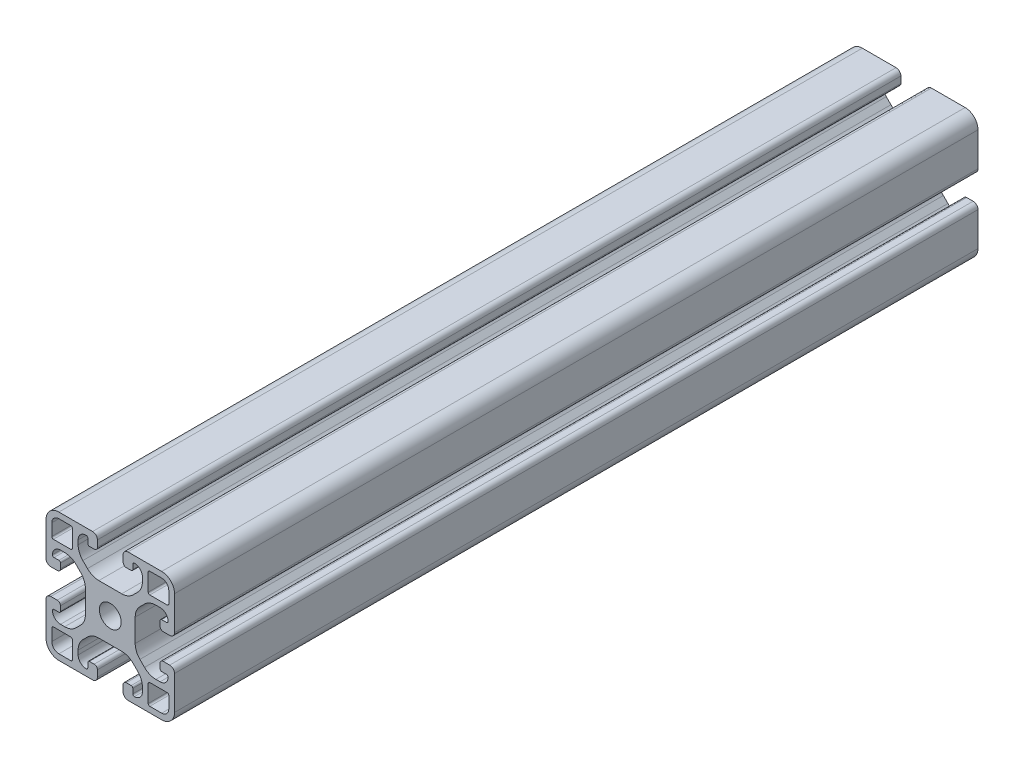
SolidWorks part; units mm, degrees
ref_plane "Front Plane" through (0, 0, 0) normal (0, 0, 1) x (1, 0, 0)
ref_plane "Top Plane" through (0, 0, 0) normal (0, 1, 0) x (1, 0, 0)
ref_plane "Right Plane" through (0, 0, 0) normal (1, 0, 0) x (0, 0, -1)
sketch "Sketch1" plane through (0, 0, 0) normal (0, 0, 1) x (1, 0, 0)
  line L0 (1.8, 4) -> (1.8, 7.7)
  line L1 (2.3, 8.2) -> (7.7, 8.2)
  line L2 (8.2, 7.7) -> (8.2, 2.3)
  line L3 (7.7, 1.8) -> (4, 1.8)
  line L4 (4, 38.2) -> (7.7, 38.2)
  line L5 (8.2, 37.7) -> (8.2, 32.3)
  line L6 (7.7, 31.8) -> (2.3, 31.8)
  line L7 (1.8, 32.3) -> (1.8, 36)
  line L8 (31.8, 32.3) -> (31.8, 37.7)
  line L9 (32.3, 38.2) -> (36, 38.2)
  line L10 (38.2, 36) -> (38.2, 32.3)
  line L11 (37.7, 31.8) -> (32.3, 31.8)
  line L12 (32.3, 8.2) -> (37.7, 8.2)
  line L13 (38.2, 7.7) -> (38.2, 4)
  line L14 (36, 1.8) -> (32.3, 1.8)
  line L15 (31.8, 2.3) -> (31.8, 7.7)
  line L16 (0, 36) -> (0, 25.5)
  line L17 (1.5, 24) -> (3.5, 24)
  line L18 (4.5, 25) -> (4.5, 26.5)
  line L19 (4, 27) -> (2.5, 27)
  line L20 (4.5, 30) -> (5.8076, 30)
  line L21 (9.3431, 28.5355) -> (10.7855, 27.0931)
  line L22 (12.25, 23.5576) -> (12.25, 16.4424)
  line L23 (10.7855, 12.9069) -> (9.3431, 11.4645)
  line L24 (5.8076, 10) -> (4.5, 10)
  line L25 (2.5, 13) -> (4, 13)
  line L26 (4.5, 13.5) -> (4.5, 15)
  line L27 (3.5, 16) -> (1.5, 16)
  line L28 (0, 14.5) -> (0, 4)
  line L29 (4, 0) -> (14.5, 0)
  line L30 (16, 1.5) -> (16, 3.5)
  line L31 (15, 4.5) -> (13.5, 4.5)
  line L32 (13, 4) -> (13, 2.5)
  line L33 (10, 4.5) -> (10, 5.8076)
  line L34 (11.4645, 9.3431) -> (12.9069, 10.7855)
  line L35 (16.4424, 12.25) -> (23.5576, 12.25)
  line L36 (27.0931, 10.7855) -> (28.5355, 9.3431)
  line L37 (30, 5.8076) -> (30, 4.5)
  line L38 (27, 2.5) -> (27, 4)
  line L39 (26.5, 4.5) -> (25, 4.5)
  line L40 (24, 3.5) -> (24, 1.5)
  line L41 (25.5, 0) -> (36, 0)
  line L42 (40, 4) -> (40, 14.5)
  line L43 (38.5, 16) -> (36.5, 16)
  line L44 (35.5, 15) -> (35.5, 13.5)
  line L45 (36, 13) -> (37.5, 13)
  line L46 (35.5, 10) -> (34.1924, 10)
  line L47 (30.6569, 11.4645) -> (29.2145, 12.9069)
  line L48 (27.75, 16.4424) -> (27.75, 23.5576)
  line L49 (29.2145, 27.0931) -> (30.6569, 28.5355)
  line L50 (34.1924, 30) -> (35.5, 30)
  line L51 (37.5, 27) -> (36, 27)
  line L52 (35.5, 26.5) -> (35.5, 25)
  line L53 (36.5, 24) -> (38.5, 24)
  line L54 (40, 25.5) -> (40, 36)
  line L55 (36, 40) -> (25.5, 40)
  line L56 (24, 38.5) -> (24, 36.5)
  line L57 (25, 35.5) -> (26.5, 35.5)
  line L58 (27, 36) -> (27, 37.5)
  line L59 (30, 35.5) -> (30, 34.1924)
  line L60 (28.5355, 30.6569) -> (27.0931, 29.2145)
  line L61 (23.5576, 27.75) -> (16.4424, 27.75)
  line L62 (12.9069, 29.2145) -> (11.4645, 30.6569)
  line L63 (10, 34.1924) -> (10, 35.5)
  line L64 (13, 37.5) -> (13, 36)
  line L65 (13.5, 35.5) -> (15, 35.5)
  line L66 (16, 36.5) -> (16, 38.5)
  line L67 (14.5, 40) -> (4, 40)
  arc A0 (1.8, 7.7) -> (2.3, 8.2) centre (2.3, 7.7) cw
  arc A1 (7.7, 8.2) -> (8.2, 7.7) centre (7.7, 7.7) cw
  arc A2 (8.2, 2.3) -> (7.7, 1.8) centre (7.7, 2.3) cw
  arc A3 (4, 1.8) -> (1.8, 4) centre (4, 4) cw
  arc A4 (1.8, 36) -> (4, 38.2) centre (4, 36) cw
  arc A5 (7.7, 38.2) -> (8.2, 37.7) centre (7.7, 37.7) cw
  arc A6 (8.2, 32.3) -> (7.7, 31.8) centre (7.7, 32.3) cw
  arc A7 (2.3, 31.8) -> (1.8, 32.3) centre (2.3, 32.3) cw
  circle A8 centre (20, 20) radius 3.4
  arc A9 (31.8, 37.7) -> (32.3, 38.2) centre (32.3, 37.7) cw
  arc A10 (36, 38.2) -> (38.2, 36) centre (36, 36) cw
  arc A11 (38.2, 32.3) -> (37.7, 31.8) centre (37.7, 32.3) cw
  arc A12 (32.3, 31.8) -> (31.8, 32.3) centre (32.3, 32.3) cw
  arc A13 (31.8, 7.7) -> (32.3, 8.2) centre (32.3, 7.7) cw
  arc A14 (37.7, 8.2) -> (38.2, 7.7) centre (37.7, 7.7) cw
  arc A15 (38.2, 4) -> (36, 1.8) centre (36, 4) cw
  arc A16 (32.3, 1.8) -> (31.8, 2.3) centre (32.3, 2.3) cw
  arc A17 (0, 25.5) -> (1.5, 24) centre (1.5, 25.5) ccw
  arc A18 (3.5, 24) -> (4.5, 25) centre (3.5, 25) ccw
  arc A19 (4.5, 26.5) -> (4, 27) centre (4, 26.5) ccw
  arc A20 (2.5, 27) -> (2, 27.5) centre (2.5, 27.5) cw
  arc A21 (2, 27.5) -> (4.5, 30) centre (4.5, 27.5) cw
  arc A22 (5.8076, 30) -> (9.3431, 28.5355) centre (5.8076, 25) cw
  arc A23 (10.7855, 27.0931) -> (12.25, 23.5576) centre (7.25, 23.5576) cw
  arc A24 (12.25, 16.4424) -> (10.7855, 12.9069) centre (7.25, 16.4424) cw
  arc A25 (9.3431, 11.4645) -> (5.8076, 10) centre (5.8076, 15) cw
  arc A26 (4.5, 10) -> (2, 12.5) centre (4.5, 12.5) cw
  arc A27 (2, 12.5) -> (2.5, 13) centre (2.5, 12.5) cw
  arc A28 (4, 13) -> (4.5, 13.5) centre (4, 13.5) ccw
  arc A29 (4.5, 15) -> (3.5, 16) centre (3.5, 15) ccw
  arc A30 (1.5, 16) -> (0, 14.5) centre (1.5, 14.5) ccw
  arc A31 (0, 4) -> (4, 0) centre (4, 4) ccw
  arc A32 (14.5, 0) -> (16, 1.5) centre (14.5, 1.5) ccw
  arc A33 (16, 3.5) -> (15, 4.5) centre (15, 3.5) ccw
  arc A34 (13.5, 4.5) -> (13, 4) centre (13.5, 4) ccw
  arc A35 (13, 2.5) -> (12.5, 2) centre (12.5, 2.5) cw
  arc A36 (12.5, 2) -> (10, 4.5) centre (12.5, 4.5) cw
  arc A37 (10, 5.8076) -> (11.4645, 9.3431) centre (15, 5.8076) cw
  arc A38 (12.9069, 10.7855) -> (16.4424, 12.25) centre (16.4424, 7.25) cw
  arc A39 (23.5576, 12.25) -> (27.0931, 10.7855) centre (23.5576, 7.25) cw
  arc A40 (28.5355, 9.3431) -> (30, 5.8076) centre (25, 5.8076) cw
  arc A41 (30, 4.5) -> (27.5, 2) centre (27.5, 4.5) cw
  arc A42 (27.5, 2) -> (27, 2.5) centre (27.5, 2.5) cw
  arc A43 (27, 4) -> (26.5, 4.5) centre (26.5, 4) ccw
  arc A44 (25, 4.5) -> (24, 3.5) centre (25, 3.5) ccw
  arc A45 (24, 1.5) -> (25.5, 0) centre (25.5, 1.5) ccw
  arc A46 (36, 0) -> (40, 4) centre (36, 4) ccw
  arc A47 (40, 14.5) -> (38.5, 16) centre (38.5, 14.5) ccw
  arc A48 (36.5, 16) -> (35.5, 15) centre (36.5, 15) ccw
  arc A49 (35.5, 13.5) -> (36, 13) centre (36, 13.5) ccw
  arc A50 (37.5, 13) -> (38, 12.5) centre (37.5, 12.5) cw
  arc A51 (38, 12.5) -> (35.5, 10) centre (35.5, 12.5) cw
  arc A52 (34.1924, 10) -> (30.6569, 11.4645) centre (34.1924, 15) cw
  arc A53 (29.2145, 12.9069) -> (27.75, 16.4424) centre (32.75, 16.4424) cw
  arc A54 (27.75, 23.5576) -> (29.2145, 27.0931) centre (32.75, 23.5576) cw
  arc A55 (30.6569, 28.5355) -> (34.1924, 30) centre (34.1924, 25) cw
  arc A56 (35.5, 30) -> (38, 27.5) centre (35.5, 27.5) cw
  arc A57 (38, 27.5) -> (37.5, 27) centre (37.5, 27.5) cw
  arc A58 (36, 27) -> (35.5, 26.5) centre (36, 26.5) ccw
  arc A59 (35.5, 25) -> (36.5, 24) centre (36.5, 25) ccw
  arc A60 (38.5, 24) -> (40, 25.5) centre (38.5, 25.5) ccw
  arc A61 (40, 36) -> (36, 40) centre (36, 36) ccw
  arc A62 (25.5, 40) -> (24, 38.5) centre (25.5, 38.5) ccw
  arc A63 (24, 36.5) -> (25, 35.5) centre (25, 36.5) ccw
  arc A64 (26.5, 35.5) -> (27, 36) centre (26.5, 36) ccw
  arc A65 (27, 37.5) -> (27.5, 38) centre (27.5, 37.5) cw
  arc A66 (27.5, 38) -> (30, 35.5) centre (27.5, 35.5) cw
  arc A67 (30, 34.1924) -> (28.5355, 30.6569) centre (25, 34.1924) cw
  arc A68 (27.0931, 29.2145) -> (23.5576, 27.75) centre (23.5576, 32.75) cw
  arc A69 (16.4424, 27.75) -> (12.9069, 29.2145) centre (16.4424, 32.75) cw
  arc A70 (11.4645, 30.6569) -> (10, 34.1924) centre (15, 34.1924) cw
  arc A71 (10, 35.5) -> (12.5, 38) centre (12.5, 35.5) cw
  arc A72 (12.5, 38) -> (13, 37.5) centre (12.5, 37.5) cw
  arc A73 (13, 36) -> (13.5, 35.5) centre (13.5, 36) ccw
  arc A74 (15, 35.5) -> (16, 36.5) centre (15, 36.5) ccw
  arc A75 (16, 38.5) -> (14.5, 40) centre (14.5, 38.5) ccw
  arc A76 (4, 40) -> (0, 36) centre (4, 36) ccw
  dimension "D1" = 20
  dimension "D2" = 20
  dimension "D3" = 6.8
  dimension "D4" = 15.5
  dimension "D5" = 15.5
extrude "Boss-Extrude1" add sketch "Sketch1" against normal blind 250
